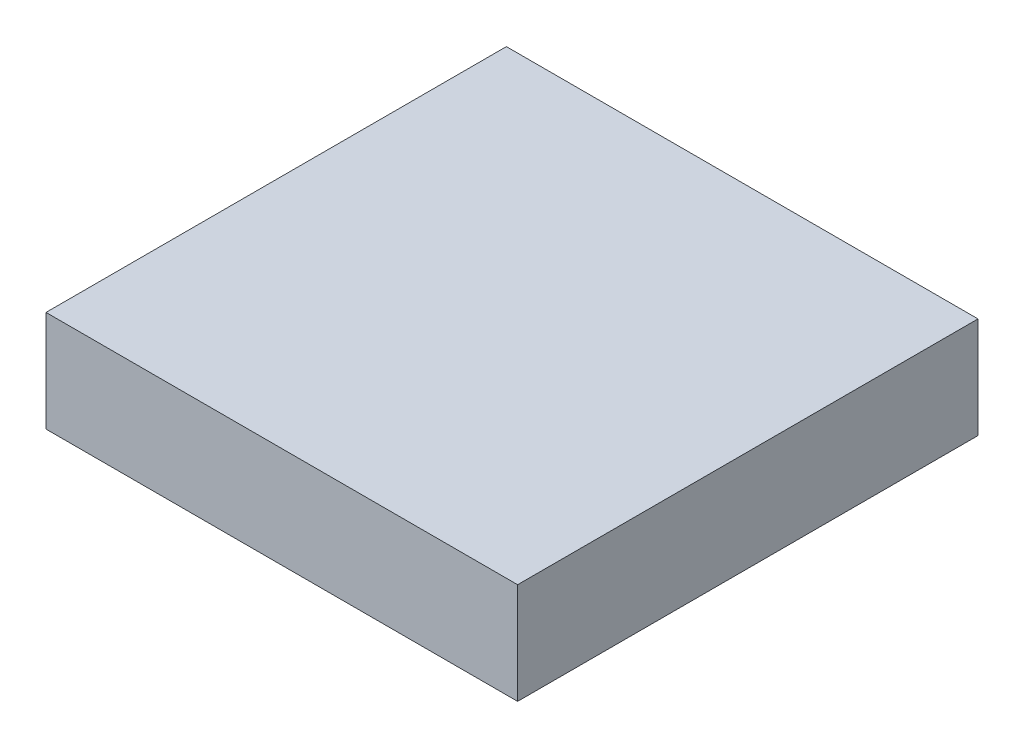
SolidWorks part; units mm, degrees
ref_plane "Front Plane" through (0, 0, 0) normal (0, 0, 1) x (1, 0, 0)
ref_plane "Top Plane" through (0, 0, 0) normal (0, 1, 0) x (1, 0, 0)
ref_plane "Right Plane" through (0, 0, 0) normal (1, 0, 0) x (0, 0, -1)
sketch "Sketch1" plane through (0, 0, 0) normal (0, 1, 0) x (1, 0, 0)
  line L1 (-53.34, 52.07) -> (53.34, 52.07)
  line L2 (-53.34, 52.07) -> (-53.34, -52.07)
  line L3 (-53.34, -52.07) -> (53.34, -52.07)
  line L4 (53.34, 52.07) -> (53.34, -52.07)
  line L5 (-53.34, 52.07) -> (53.34, -52.07) construction
  line L6 (-53.34, -52.07) -> (53.34, 52.07) construction
  point P0 (0, 0)
  dimension "D1" = 106.68
  dimension "D2" = 104.14
extrude "Boss-Extrude1" add sketch "Sketch1" along normal blind 22.86
